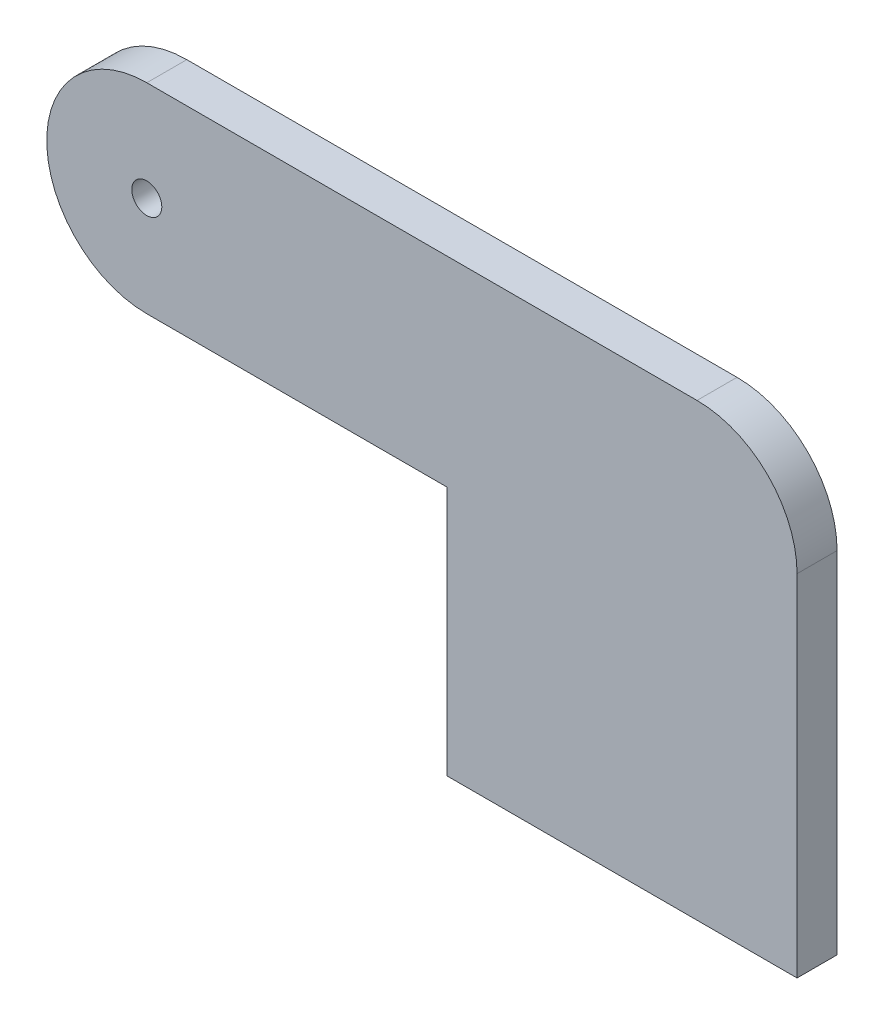
SolidWorks part; units mm, degrees
ref_plane "Front Plane" through (0, 0, 0) normal (0, 0, 1) x (1, 0, 0)
ref_plane "Top Plane" through (0, 0, 0) normal (0, 1, 0) x (1, 0, 0)
ref_plane "Right Plane" through (0, 0, 0) normal (1, 0, 0) x (0, 0, -1)
sketch "Sketch1" plane through (0, 0, 0) normal (0, 0, 1) x (1, 0, 0)
  line L1 (0, 10) -> (55, 10)
  line L2 (0, -10) -> (30, -10)
  line L5 (30, -10) -> (30, -35)
  line L6 (30, -35) -> (65, -35)
  line L7 (65, 0) -> (65, -35)
  arc A0 (0, 10) -> (0, -10) centre (0, 0) ccw
  arc A1 (65, 0) -> (55, 10) centre (55, 0) ccw
  circle A2 centre (0, 0) radius 1.5
  point P3 (35, 0)
  point P8 (51.9513, 10)
  dimension "D2" = 10
  dimension "D7" = 10
  dimension "D9" = 3
  dimension "D3" = 35
  dimension "D4" = 30
  dimension "D6" = 35
  dimension "D8" = 90
extrude "Boss-Extrude1" add sketch "Sketch1" along normal blind 4
